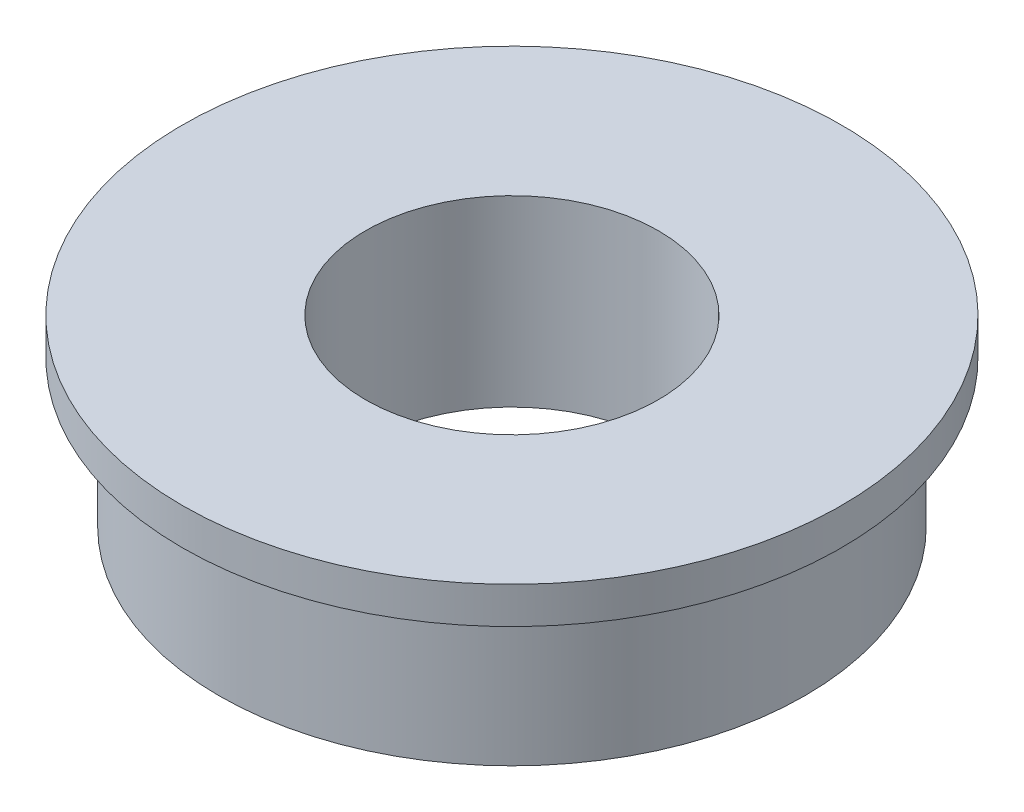
SolidWorks part; units mm, degrees
ref_plane "前视基准面" through (0, 0, 0) normal (0, 0, 1) x (1, 0, 0)
ref_plane "上视基准面" through (0, 0, 0) normal (0, 1, 0) x (1, 0, 0)
ref_plane "右视基准面" through (0, 0, 0) normal (1, 0, 0) x (0, 0, -1)
sketch "Sketch1" plane through (0, 0, 0) normal (0, 1, 0) x (1, 0, 0)
  circle A0 centre (0, 0) radius 4
  circle A1 centre (0, 0) radius 8
extrude "Boss-Extrude1" add sketch "Sketch1" along normal blind 4
sketch "Sketch2" plane through (0, 4, 0) normal (0, 1, 0) x (1, 0, 0)
  circle A0 centre (0, 0) radius 4
  circle A1 centre (0, 0) radius 9
extrude "Boss-Extrude2" add sketch "Sketch2" along normal blind 1
